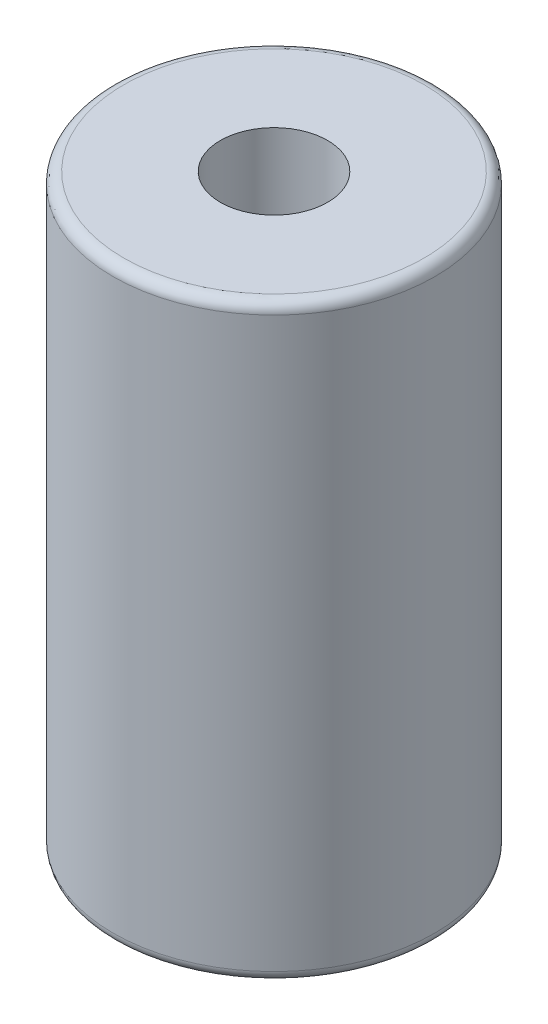
SolidWorks part; units mm, degrees
ref_plane "Front Plane" through (0, 0, 0) normal (0, 0, 1) x (1, 0, 0)
ref_plane "Top Plane" through (0, 0, 0) normal (0, 1, 0) x (1, 0, 0)
ref_plane "Right Plane" through (0, 0, 0) normal (1, 0, 0) x (0, 0, -1)
sketch "Sketch1" plane through (0, 0, 0) normal (0, 1, 0) x (1, 0, 0)
  circle A0 centre (0, 0) radius 1.5
  circle A1 centre (0, 0) radius 0.5
  dimension "D1" = 3
  dimension "D2" = 1
extrude "Boss-Extrude1" add sketch "Sketch1" along normal blind 5.5
fillet "Fillet1" radius 0.1 2 edges at (0, 0, 1.5) (0, 5.5, 1.5)
